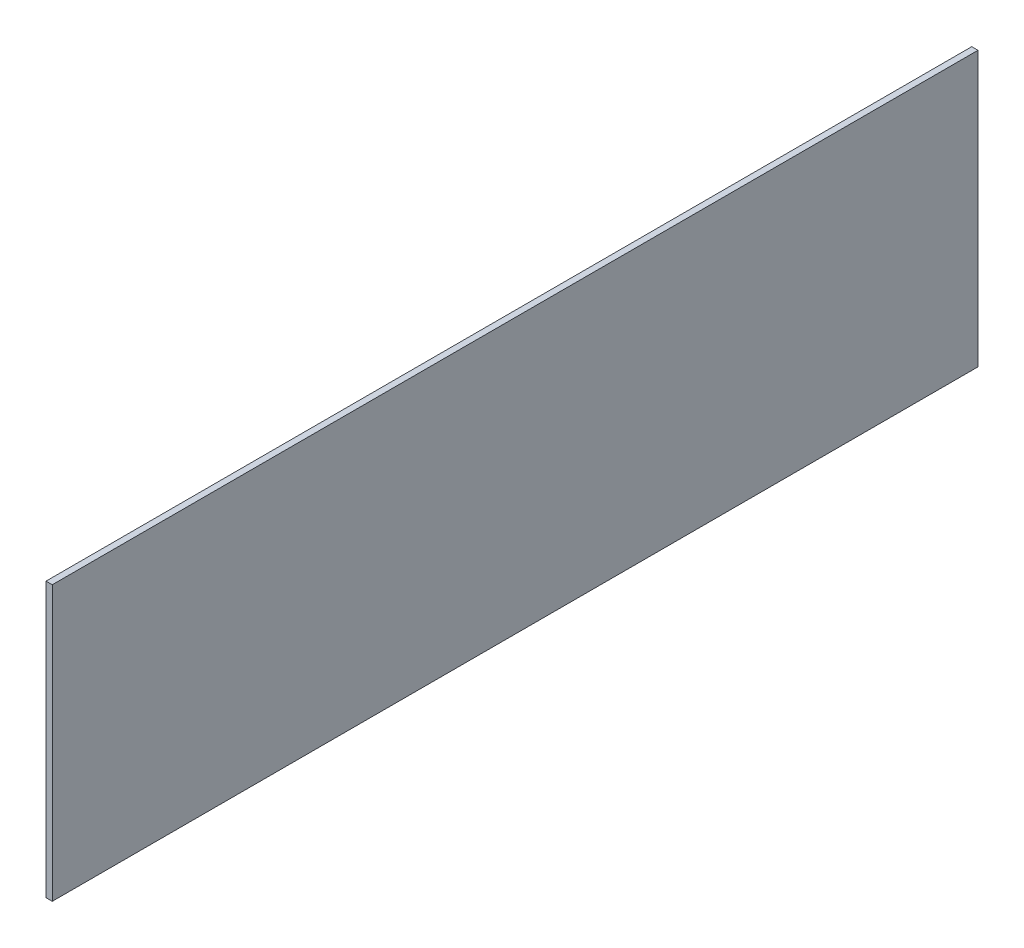
SolidWorks part; units mm, degrees
ref_plane "Front Plane" through (0, 0, 0) normal (0, 0, 1) x (1, 0, 0)
ref_plane "Top Plane" through (0, 0, 0) normal (0, 1, 0) x (1, 0, 0)
ref_plane "Right Plane" through (0, 0, 0) normal (1, 0, 0) x (0, 0, -1)
sketch "Sketch1" plane through (0, 0, 0) normal (0, 0, 1) x (1, 0, 0)
  line L1 (-61.2632, 127.5789) -> (-49.2632, 127.5789)
  line L2 (-61.2632, 127.5789) -> (-61.2632, -398.4211)
  line L3 (-61.2632, -398.4211) -> (-49.2632, -398.4211)
  line L4 (-49.2632, 127.5789) -> (-49.2632, -398.4211)
  dimension "D1" = 12
  dimension "D2" = 526
extrude "Boss-Extrude1" add sketch "Sketch1" along normal blind 1776
